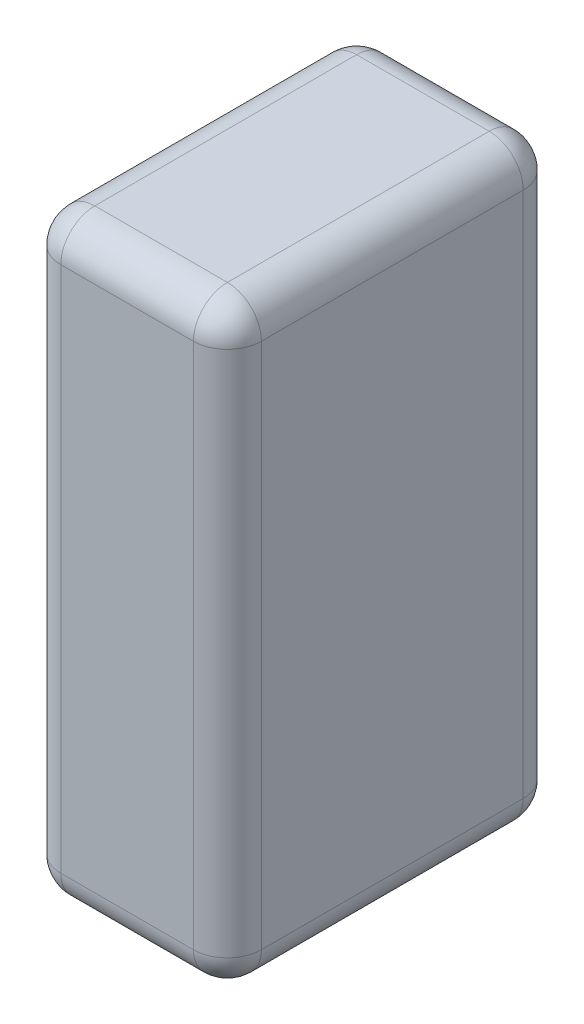
SolidWorks part; units mm, degrees
ref_plane "Front Plane" through (0, 0, 0) normal (0, 0, 1) x (1, 0, 0)
ref_plane "Top Plane" through (0, 0, 0) normal (0, 1, 0) x (1, 0, 0)
ref_plane "Right Plane" through (0, 0, 0) normal (1, 0, 0) x (0, 0, -1)
sketch "Sketch1" plane through (0, 0, 0) normal (0, 1, 0) x (1, 0, 0)
  line L1 (-2.95, 4.85) -> (2.95, 4.85)
  line L2 (-2.95, 4.85) -> (-2.95, -4.85)
  line L3 (-2.95, -4.85) -> (2.95, -4.85)
  line L4 (2.95, 4.85) -> (2.95, -4.85)
  line L5 (-2.95, 4.85) -> (2.95, -4.85) construction
  line L6 (-2.95, -4.85) -> (2.95, 4.85) construction
  point P0 (0, 0)
  dimension "D1" = 5.9
  dimension "D2" = 9.7
extrude "Boss-Extrude1" add sketch "Sketch1" along normal blind 17.5
fillet "Fillet1" radius 1 12 edges at (-2.95, 8.75, -4.85) (-2.95, 17.5, 0) (-2.95, 8.75, 4.85) (-2.95, 0, 0) (0, 0, -4.85) (2.95, 0, 0) (0, 0, 4.85) (0, 17.5, -4.85) (2.95, 17.5, 0) (0, 17.5, 4.85) (2.95, 8.75, -4.85) (2.95, 8.75, 4.85)
